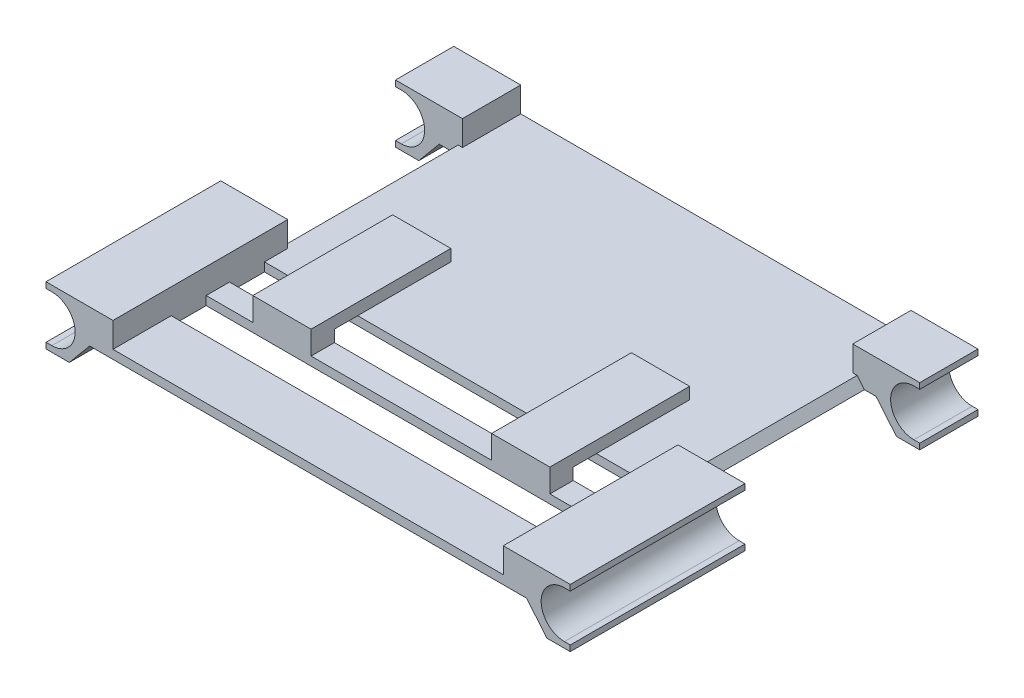
SolidWorks part; units mm, degrees
ref_plane "Plan de face" through (0, 0, 0) normal (0, 0, 1) x (1, 0, 0)
ref_plane "Plan de dessus" through (0, 0, 0) normal (0, 1, 0) x (1, 0, 0)
ref_plane "Plan de droite" through (0, 0, 0) normal (1, 0, 0) x (0, 0, -1)
sketch "Esquisse1" plane through (0, 0, 0) normal (0, 0, 1) x (1, 0, 0)
  line L0 (44.5, -0.5) -> (39.25, -0.5) construction
  line L1 (0.5, -4.5) -> (0, -4.5)
  line L2 (-1.0664, -2.9) -> (51.0361, -2.9) construction
  line L3 (0.5, -0.5) -> (0.5, -10.5833) construction
  line L4 (44.5, -0.5) -> (44.5, -11.5333) construction
  line L5 (44.5, -4.5) -> (45, -4.5)
  line L6 (45, -4.5) -> (45, -5)
  line L7 (45, -5) -> (44.5, -5)
  line L8 (0, -4.5) -> (0, -5)
  line L9 (0, -5) -> (0.5, -5)
  line L10 (0.5, -5) -> (2, -5)
  line L11 (44.5, -5) -> (43, -5)
  line L12 (2, -5) -> (3.75, -2.9)
  line L13 (43, -5) -> (41.25, -2.9)
  line L14 (0.5, -0.5) -> (0, -0.5)
  line L16 (0, 0) -> (5.75, 0)
  line L18 (-1.0664, -2.15) -> (47.7682, -2.15) construction
  line L19 (40.625, -2.15) -> (4.375, -2.15)
  line L20 (3.75, -2.9) -> (41.25, -2.9)
  line L21 (40.625, -2.15) -> (39.25, -0.5)
  line L22 (4.375, -2.15) -> (5.75, -0.5)
  line L23 (39.25, -0.5) -> (39.25, 0)
  line L24 (5.75, -0.5) -> (5.75, 0)
  line L25 (39.25, 0) -> (44.5, 0)
  line L26 (5.75, -0.5) -> (0.5, -0.5) construction
  line L27 (44.5, -0.5) -> (45, -0.5)
  line L28 (45, -0.5) -> (45, 0)
  line L29 (45, 0) -> (44.5, 0)
  line L30 (0, -0.5) -> (0, 0)
  arc A0 (0.5, -4.5) -> (0.5, -0.5) centre (0.5, -2.5) ccw
  arc A1 (44.5, -0.5) -> (44.5, -4.5) centre (44.5, -2.5) ccw
  dimension "D1" = 4
  dimension "D2" = 4
  dimension "D3" = 0.5
  dimension "D4" = 0.5
  dimension "D5" = 1.5
  dimension "D6" = 1.5
  dimension "D7" = 33.5
  dimension "D8" = 44
  dimension "D9" = 0.75
  dimension "D10" = 2
  dimension "D11" = 2
  dimension "D12" = 0.5
  dimension "D13" = 2.9
  dimension "D14" = 5.75
extrude "Boss.-Extru.1" add sketch "Esquisse1" along normal blind 5
sketch "Esquisse3" plane through (0, 0, 5) normal (0, 0, 1) x (1, 0, 0)
  line L0 (40.25, -2.9) -> (39.625, -2.15)
  line L1 (2.5, -2.7485) -> (2.5, 0.8222) construction
  line L3 (3.75, -2.9) -> (41.25, -2.9) construction
  line L6 (40.625, -2.15) -> (4.375, -2.15) construction
  line L8 (5.375, -2.15) -> (4.75, -2.9)
  line L9 (40.25, -2.9) -> (4.75, -2.9)
  line L10 (2.5, -2.15) -> (-999.375, -2.15) construction
  line L11 (5.375, -2.15) -> (39.625, -2.15)
  dimension "D1" = 1
  dimension "D2" = 1
  dimension "D3" = 1
  dimension "D4" = 1
extrude "Boss.-Extru.2" add sketch "Esquisse3" along normal blind 15
sketch "Esquisse4" plane through (0, 0, 20) normal (0, 0, 1) x (1, 0, 0)
  line L0 (44.5, -0.5) -> (39.25, -0.5) construction
  line L1 (0.5, -4.5) -> (0, -4.5)
  line L2 (-1.8693, -2.9) -> (50.2332, -2.9) construction
  line L3 (0.5, -0.5) -> (0.5, -10.5833) construction
  line L4 (44.5, -0.5) -> (44.5, -11.5333) construction
  line L5 (44.5, -4.5) -> (45, -4.5)
  line L6 (45, -4.5) -> (45, -5)
  line L7 (45, -5) -> (44.5, -5)
  line L8 (0, -4.5) -> (0, -5)
  line L9 (0, -5) -> (0.5, -5)
  line L10 (0.5, -5) -> (2, -5)
  line L11 (44.5, -5) -> (43, -5)
  line L12 (2, -5) -> (3.75, -2.9)
  line L13 (43, -5) -> (41.25, -2.9)
  line L14 (0.5, -0.5) -> (0, -0.5)
  line L15 (0, 0) -> (5.75, 0)
  line L16 (-1.8693, -2.15) -> (46.9653, -2.15) construction
  line L17 (40.625, -2.15) -> (4.375, -2.15)
  line L18 (3.75, -2.9) -> (41.25, -2.9)
  line L19 (40.625, -2.15) -> (39.25, -0.5)
  line L20 (4.375, -2.15) -> (5.75, -0.5)
  line L21 (39.25, -0.5) -> (39.25, 0)
  line L22 (5.75, -0.5) -> (5.75, 0)
  line L23 (39.25, 0) -> (43.6971, 0)
  line L24 (5.75, -0.5) -> (0.5, -0.5) construction
  line L25 (44.5, -0.5) -> (45, -0.5)
  line L26 (45, -0.5) -> (45, 0)
  line L27 (45, 0) -> (43.6971, 0)
  line L28 (0, -0.5) -> (0, 0)
  line L29 (4.75, -2.9) -> (40.25, -2.9) construction
  arc A0 (0.5, -4.5) -> (0.5, -0.5) centre (0.5, -2.5) ccw
  arc A1 (44.5, -0.5) -> (44.5, -4.5) centre (44.5, -2.5) ccw
  dimension "D4" = 2
  dimension "D8" = 2
  dimension "D1" = 44
  dimension "D2" = 5.75
  dimension "D3" = 5
  dimension "D5" = 36.25
  dimension "D6" = 37.5
  dimension "D7" = 5.75
  dimension "D9" = 5
  dimension "D10" = 1.5
  dimension "D11" = 0.5
  dimension "D12" = 1.5
  dimension "D13" = 0.5
  dimension "D14" = 1
extrude "Boss.-Extru.3" add sketch "Esquisse4" along normal blind 15
sketch "Esquisse5" plane through (0, 0, 0) normal (0, 1, 0) x (1, 0, 0)
  line L0 (45, -35) -> (39.25, -35) construction
  line L1 (39.25, -20) -> (41.6967, -20)
  line L2 (39.25, -20) -> (39.25, -35)
  line L3 (39.25, -35) -> (41.6967, -35)
  line L4 (41.6967, -20) -> (41.6967, -35)
  line L5 (5.75, -35) -> (5.75, -20) construction
  line L6 (5.75, -20) -> (2.875, -20)
  line L7 (5.75, -20) -> (5.75, -35)
  line L8 (5.75, -35) -> (2.875, -35)
  line L9 (2.875, -20) -> (2.875, -35)
  line L10 (5.75, -20) -> (0, -20) construction
  line L11 (5.75, -35) -> (0, -35) construction
  line L12 (5.75, 0) -> (0, 0) construction
  line L13 (5.75, -5) -> (3.6263, -5)
  line L14 (5.75, -5) -> (5.75, 0)
  line L15 (5.75, 0) -> (3.6263, 0)
  line L16 (3.6263, -5) -> (3.6263, 0)
  line L17 (45, 0) -> (39.25, 0) construction
  line L18 (39.25, -5) -> (41.2351, -5)
  line L19 (39.25, -5) -> (39.25, 0)
  line L20 (39.25, 0) -> (41.2351, 0)
  line L21 (41.2351, -5) -> (41.2351, 0)
extrude "Boss.-Extru.4" add sketch "Esquisse5" against normal blind 2.5
sketch "Esquisse6" plane through (0, -2.15, 0) normal (0, 1, 0) x (1, 0, 0)
  line L0 (39.25, -35) -> (39.25, -20) construction
  line L1 (39.25, -30) -> (5.75, -30)
  line L2 (39.25, -30) -> (39.25, -27)
  line L3 (39.25, -27) -> (5.75, -27)
  line L4 (5.75, -30) -> (5.75, -27)
  line L5 (5.75, -20) -> (5.75, -35) construction
  line L6 (39.25, -35) -> (5.75, -35) construction
  line L8 (39.25, -25) -> (5.75, -25)
  line L9 (39.25, -25) -> (39.25, -22)
  line L10 (39.25, -22) -> (5.75, -22)
  line L11 (5.75, -25) -> (5.75, -22)
  dimension "D1" = 5
  dimension "D2" = 3
  dimension "D3" = 3
  dimension "D4" = 2
extrude "Enlèv. mat.-Extru.1" cut sketch "Esquisse6" against normal blind 2.5
sketch "Esquisse8" plane through (0, -2.15, 0) normal (0, 1, 0) x (1, 0, 0)
  line L0 (39.25, -27) -> (5.75, -27) construction
  line L1 (35.25, -27) -> (30.25, -27)
  line L2 (35.25, -27) -> (35.25, -25)
  line L3 (35.25, -25) -> (30.25, -25)
  line L4 (30.25, -27) -> (30.25, -25)
  line L5 (5.75, -25) -> (39.25, -25) construction
  line L6 (39.25, -27) -> (39.25, -25) construction
  line L7 (14.75, -27) -> (9.75, -27)
  line L8 (14.75, -27) -> (14.75, -25)
  line L9 (14.75, -25) -> (9.75, -25)
  line L10 (9.75, -27) -> (9.75, -25)
  line L11 (5.75, -25) -> (5.75, -27) construction
  dimension "D1" = 5
  dimension "D2" = 5
  dimension "D3" = 4
  dimension "D4" = 4
extrude "Boss.-Extru.5" add sketch "Esquisse8" along normal blind 1
sketch "Esquisse9" plane through (0, -1.15, 0) normal (0, 1, 0) x (1, 0, 0)
  line L0 (30.25, -25) -> (30.25, -27) construction
  line L1 (35.25, -27) -> (30.25, -27)
  line L2 (35.25, -27) -> (35.25, -15)
  line L3 (35.25, -15) -> (30.25, -15)
  line L4 (30.25, -27) -> (30.25, -15)
  line L5 (14.75, -27) -> (9.75, -27)
  line L6 (14.75, -27) -> (14.75, -15)
  line L7 (14.75, -15) -> (9.75, -15)
  line L8 (9.75, -27) -> (9.75, -15)
  line L9 (9.75, -25) -> (9.75, -27) construction
  dimension "D1" = 0
  dimension "D2" = 0
  dimension "D3" = 12
  dimension "D4" = 12
extrude "Boss.-Extru.6" add sketch "Esquisse9" along normal blind 1
